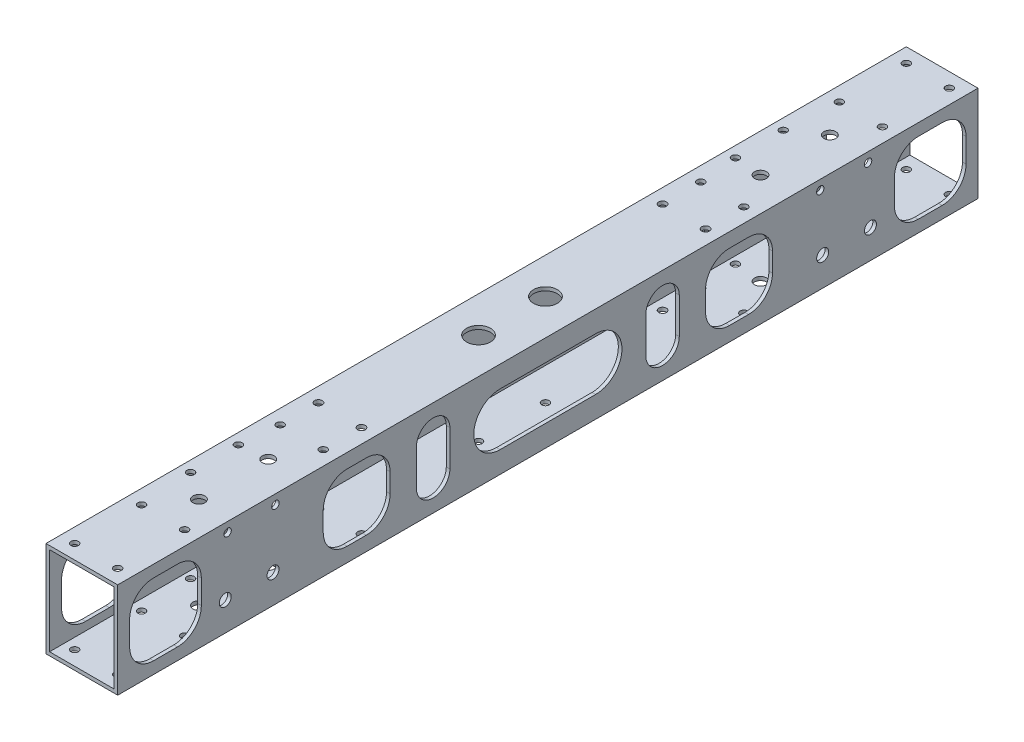
SolidWorks part; units mm, degrees
material "6061 合金"
ref_plane "前视基准面" through (0, 0, 0) normal (0, 0, 1) x (1, 0, 0)
ref_plane "上视基准面" through (0, 0, 0) normal (0, 1, 0) x (1, 0, 0)
ref_plane "右视基准面" through (0, 0, 0) normal (1, 0, 0) x (0, 0, -1)
other "Configuration Table"
sketch "草图1" plane through (0, 0, 0) normal (0, 0, 1) x (1, 0, 0)
  line L1 (-15, 20) -> (15, 20)
  line L2 (-15, 20) -> (-15, -20)
  line L3 (-15, -20) -> (15, -20)
  line L4 (15, 20) -> (15, -20)
  line L5 (-15, 20) -> (15, -20) construction
  line L6 (-15, -20) -> (15, 20) construction
  line L7 (-13.5, 18.5) -> (13.5, 18.5)
  line L8 (-13.5, 18.5) -> (-13.5, -18.5)
  line L9 (-13.5, -18.5) -> (13.5, -18.5)
  line L10 (13.5, 18.5) -> (13.5, -18.5)
  line L11 (-13.5, 18.5) -> (13.5, -18.5) construction
  line L12 (-13.5, -18.5) -> (13.5, 18.5) construction
  point P0 (0, 0)
  point P6 (0, 0)
  dimension "D1" = 30
  dimension "D2" = 1.5
  dimension "D3" = 1.5
  dimension "D4" = 40
extrude "凸台-拉伸1" add sketch "草图1" along normal mid plane 360
sketch "草图2" plane through (0, -20, 0) normal (0, -1, 0) x (1, 0, 0)
  line L0 (0, -14) -> (0, 14) construction
  circle A0 centre (0, 14) radius 1.55
  circle A1 centre (0, -14) radius 1.55
  dimension "D1" = 3.1
  dimension "D2" = 28
extrude "切除-拉伸1" cut sketch "草图2" against normal blind 10
sketch "草图3" plane through (0, -20, 0) normal (0, -1, 0) x (1, 0, 0)
  circle A0 centre (-8.99, 72) radius 1.6 construction
  circle A1 centre (9.01, 72) radius 1.6 construction
  circle A2 centre (-8.99, -72) radius 1.6 construction
  circle A3 centre (9.01, -72) radius 1.6 construction
  circle A4 centre (-8.99, 72) radius 1.6
  circle A5 centre (9.01, 72) radius 1.6
  circle A6 centre (-8.99, -72) radius 1.6
  circle A7 centre (9.01, -72) radius 1.6
extrude "切除-拉伸2" cut sketch "草图3" against normal blind 40
sketch "草图4" plane through (15, 0, 0) normal (1, 0, 0) x (0, 0, -1)
  line L0 (-20, 0) -> (20, 0) construction
  line L1 (-20, 11) -> (20, 11)
  line L2 (-20, -11) -> (20, -11)
  arc A0 (-20, 11) -> (-20, -11) centre (-20, 0) ccw
  arc A1 (20, -11) -> (20, 11) centre (20, 0) ccw
  point P3 (0, 0)
  dimension "D1" = 11
  dimension "D2" = 40
extrude "切除-拉伸3" cut sketch "草图4" against normal blind 10
sketch "草图5" plane through (0, 18.5, 0) normal (0, -1, 0) x (1, 0, 0)
  circle A0 centre (0, 14) radius 5
  circle A1 centre (0, -14) radius 5
  dimension "D1" = 10
extrude "切除-拉伸4" cut sketch "草图5" against normal blind 10
sketch "草图6" plane through (-15, 0, 0) normal (-1, 0, 0) x (0, 0, 1)
  line L0 (180, 20) -> (180, -20) construction
  line L1 (140, 20) -> (180, 20) construction
  line L2 (140, 20) -> (140, -20) construction
  line L3 (140, -20) -> (180, -20) construction
  line L4 (180, 20) -> (180, -20) construction
  line L5 (140, 20) -> (180, -20) construction
  line L6 (140, -20) -> (180, 20) construction
  line L7 (180, 20) -> (-180, 20) construction
  line L8 (0, -102.9172) -> (0, 73.5105) construction
  line L9 (145, 15) -> (175, 15)
  line L10 (145, 15) -> (145, -15)
  line L11 (145, -15) -> (175, -15)
  line L12 (175, 15) -> (175, -15)
  line L13 (145, 15) -> (175, -15) construction
  line L14 (145, -15) -> (175, 15) construction
  line L15 (-145, -15) -> (-175, 15) construction
  line L16 (-145, 15) -> (-175, -15) construction
  line L17 (-140, -20) -> (-180, 20) construction
  line L18 (-140, 20) -> (-180, -20) construction
  line L19 (-180, 20) -> (-180, -20) construction
  line L20 (-140, -20) -> (-180, -20) construction
  line L21 (-140, 20) -> (-140, -20) construction
  line L22 (-140, 20) -> (-180, 20) construction
  line L23 (-175, 15) -> (-175, -15)
  line L24 (-145, -15) -> (-175, -15)
  line L25 (-145, 15) -> (-145, -15)
  line L26 (-145, 15) -> (-175, 15)
  point P0 (160, 0)
  point P9 (160, 0)
  point P26 (-160, 0)
  dimension "D1" = 30
extrude "切除-拉伸5" cut sketch "草图6" against normal blind 30
fillet "圆角1" radius 10 16 edges at (14.25, 15, -175) (14.25, 15, -145) (14.25, -15, -145) (14.25, -15, 145) (14.25, 15, 145) (14.25, 15, 175) (14.25, -15, 175) (14.25, -15, -175) (-14.25, -15, -175) (-14.25, 15, -175) (-14.25, 15, -145) (-14.25, -15, 175) (-14.25, -15, 145) (-14.25, 15, 145) (-14.25, 15, 175) (-14.25, -15, -145)
sketch "草图8" plane through (0, -20, 0) normal (0, -1, 0) x (1, 0, 0)
  line L0 (-15, -180) -> (15, -180) construction
  line L1 (-9, -174) -> (9, -174) construction
  line L2 (-9, -174) -> (-9, -146) construction
  line L3 (-9, -146) -> (9, -146) construction
  line L4 (9, -174) -> (9, -146) construction
  line L5 (225, -140) -> (-75, -140) construction
  line L6 (-47.2704, 0) -> (0, 0) construction
  line L7 (9, 174) -> (9, 146) construction
  line L8 (-9, 146) -> (9, 146) construction
  line L9 (-9, 174) -> (-9, 146) construction
  line L10 (-9, 174) -> (9, 174) construction
  circle A0 centre (-9, 88) radius 1.55
  circle A1 centre (9, 88) radius 1.55
  circle A2 centre (-9, -88) radius 1.55
  circle A3 centre (9, -88) radius 1.55
  circle A4 centre (-9, -146) radius 1.55
  circle A5 centre (9, -146) radius 1.55
  circle A6 centre (-9, -174) radius 1.55
  circle A7 centre (9, -174) radius 1.55
  circle A8 centre (9, 174) radius 1.55
  circle A9 centre (-9, 174) radius 1.55
  circle A10 centre (9, 146) radius 1.55
  circle A11 centre (-9, 146) radius 1.55
  dimension "D3" = 3.1
  dimension "D1" = 6
  dimension "D2" = 6
extrude "切除-拉伸6" cut sketch "草图8" against normal blind 40
sketch "草图9" plane through (0, 20, 0) normal (0, 1, 0) x (1, 0, 0)
  circle A0 centre (1, -103) radius 2.5
  circle A1 centre (1, -132) radius 2.5
  dimension "D1" = 5
extrude "切除-拉伸7" cut sketch "草图9" against normal blind 40
sketch "草图10" plane through (0, 20, 0) normal (0, 1, 0) x (1, 0, 0)
  circle A0 centre (1, 103) radius 2.5
  circle A1 centre (1, 132) radius 2.5
  dimension "D1" = 5
extrude "切除-拉伸8" cut sketch "草图10" against normal blind 40
sketch "草图11" plane through (-15, 0, 0) normal (-1, 0, 0) x (0, 0, 1)
  line L0 (180, 20) -> (180, -20) construction
  line L1 (76, 14) -> (84, 14)
  line L2 (66, 4) -> (66, -4)
  line L3 (76, -14) -> (84, -14)
  line L4 (94, 4) -> (94, -4)
  line L5 (66, 14) -> (94, -14) construction
  line L6 (66, -14) -> (94, 14) construction
  line L7 (180, -20) -> (-180, -20) construction
  line L12 (145, 5) -> (145, -5) construction
  line L13 (0, -51.038) -> (0, 58.2152) construction
  line L14 (-66, -14) -> (-94, 14) construction
  line L15 (-66, 14) -> (-94, -14) construction
  line L16 (-94, 4) -> (-94, -4)
  line L17 (-76, -14) -> (-84, -14)
  line L18 (-66, 4) -> (-66, -4)
  line L19 (-76, 14) -> (-84, 14)
  circle A4 centre (115, -8) radius 2.5
  circle A5 centre (135, -8) radius 2.5
  arc A6 (84, 14) -> (94, 4) centre (84, 4) cw
  arc A7 (76, 14) -> (66, 4) centre (76, 4) ccw
  arc A8 (66, -4) -> (76, -14) centre (76, -4) ccw
  arc A9 (84, -14) -> (94, -4) centre (84, -4) ccw
  arc A10 (-84, -14) -> (-94, -4) centre (-84, -4) cw
  arc A11 (-66, -4) -> (-76, -14) centre (-76, -4) cw
  arc A12 (-76, 14) -> (-66, 4) centre (-76, 4) cw
  arc A13 (-84, 14) -> (-94, 4) centre (-84, 4) ccw
  circle A14 centre (-135, -8) radius 2.5
  circle A15 centre (-115, -8) radius 2.5
  point P0 (80, 0)
  point P50 (-80, 0)
  dimension "D4" = 5
  dimension "D7" = 10
  dimension "D1" = 100
  dimension "D2" = 28
  dimension "D3" = 20
  dimension "D5" = 12
  dimension "D6" = 30
extrude "切除-拉伸9" cut sketch "草图11" against normal blind 40
sketch "草图12" plane through (-15, 0, 0) normal (-1, 0, 0) x (0, 0, 1)
  circle A0 centre (114, 16) radius 1.55
  circle A1 centre (134, 16) radius 1.55
  circle A2 centre (-134, 16) radius 1.55
  circle A3 centre (-114, 16) radius 1.55
  dimension "D1" = 3.1
extrude "切除-拉伸10" cut sketch "草图12" against normal blind 40
sketch "草图14" plane through (0, 20, 0) normal (0, 1, 0) x (1, 0, 0)
  line L0 (-15, -180) -> (-15, 180) construction
  line L1 (0, 0) -> (-38.9525, 0) construction
  circle A0 centre (-10.5, -124) radius 1.55
  circle A1 centre (-10.5, -104) radius 1.55
  circle A2 centre (-10.5, 104) radius 1.55
  circle A3 centre (-10.5, 124) radius 1.55
  circle A4 centre (1, -132) radius 2.5 construction
  dimension "D1" = 3.1
  dimension "D2" = 20
  dimension "D3" = 4.5
  dimension "D4" = 28
extrude "切除-拉伸11" cut sketch "草图14" against normal blind 50
sketch "草图15" plane through (15, 0, 0) normal (1, 0, 0) x (0, 0, -1)
  line L0 (48, 7.5) -> (48, -7.5) construction
  line L1 (55, 7.5) -> (55, -7.5)
  line L2 (41, 7.5) -> (41, -7.5)
  line L3 (0, -46.7172) -> (0, 28.3714) construction
  line L4 (-48, 7.5) -> (-48, -7.5) construction
  line L5 (-55, 7.5) -> (-55, -7.5)
  line L6 (-41, 7.5) -> (-41, -7.5)
  arc A0 (55, 7.5) -> (41, 7.5) centre (48, 7.5) ccw
  arc A1 (41, -7.5) -> (55, -7.5) centre (48, -7.5) ccw
  arc A2 (-55, 7.5) -> (-41, 7.5) centre (-48, 7.5) cw
  arc A3 (-41, -7.5) -> (-55, -7.5) centre (-48, -7.5) cw
  point P2 (48, 0)
  point P12 (-48, 0)
  dimension "D1" = 7
  dimension "D2" = 15
  dimension "D3" = 48
extrude "切除-拉伸12" cut sketch "草图15" against normal blind 40
